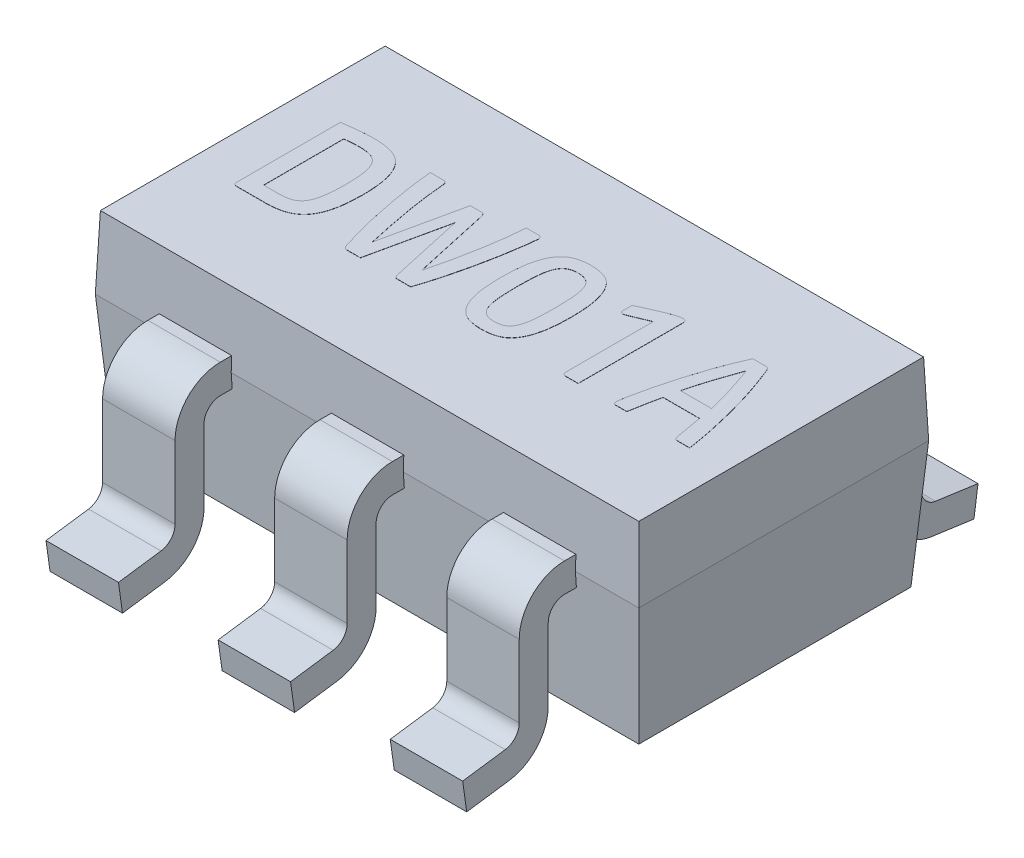
SolidWorks part; units mm, degrees
ref_plane "Front" through (0, 0, 0) normal (0, 0, 1) x (1, 0, 0)
ref_plane "Top" through (0, 0, 0) normal (0, 1, 0) x (1, 0, 0)
ref_plane "Right" through (0, 0, 0) normal (1, 0, 0) x (0, 0, -1)
sketch "Sketch1" plane through (0, 0, 0) normal (0, 1, 0) x (1, 0, 0)
  line L1 (-1.5, -0.8) -> (1.5, -0.8)
  line L2 (-1.5, -0.8) -> (-1.5, 0.8)
  line L3 (-1.5, 0.8) -> (1.5, 0.8)
  line L4 (1.5, -0.8) -> (1.5, 0.8)
  line L5 (-1.5, -0.8) -> (1.5, 0.8) construction
  line L6 (-1.5, 0.8) -> (1.5, -0.8) construction
  point P0 (0, 0)
  dimension "D1" = 3
  dimension "D2" = 1.6
extrude "Extrude1" add sketch "Sketch1" along normal blind 0.4 draft 2 and the other way blind 0.7 draft 4
ref_plane "Plane1" through (0.95, 0, 0) normal (1, 0, 0) x (0, 0, -1)
sketch "Sketch5" plane through (0.95, 0, 0) normal (1, 0, 0) x (0, 0, -1)
  line L0 (0, 0.08) -> (-0.86, 0.08)
  line L1 (-1.11, -0.17) -> (-1.11, -0.5694)
  line L2 (-1.1875, -0.6586) -> (-1.4223, -0.6916)
  line L3 (0, -0.08) -> (-0.86, -0.08)
  line L4 (0, 0.08) -> (0, -0.08) construction
  line L5 (-1.4223, -0.6916) -> (-1.4, -0.85)
  line L6 (-0.95, -0.17) -> (-0.95, -0.5694)
  line L7 (-1.1652, -0.817) -> (-1.4, -0.85)
  line L9 (10.6727, 0) -> (-10.6727, 0) construction
  line L10 (-0.7511, -0.7) -> (0.7511, -0.7) construction
  line L12 (0, 3.8593) -> (0, -3.8593) construction
  line L13 (1.1652, -0.817) -> (1.4, -0.85)
  line L14 (0.95, -0.17) -> (0.95, -0.5694)
  line L15 (1.4223, -0.6916) -> (1.4, -0.85)
  line L16 (0, -0.08) -> (0.86, -0.08)
  line L17 (1.1875, -0.6586) -> (1.4223, -0.6916)
  line L18 (1.11, -0.17) -> (1.11, -0.5694)
  line L19 (0, 0.08) -> (0.86, 0.08)
  arc A0 (-1.11, -0.5694) -> (-1.1875, -0.6586) centre (-1.2, -0.5694) cw
  arc A1 (-0.86, 0.08) -> (-1.11, -0.17) centre (-0.86, -0.17) ccw
  arc A2 (-0.86, -0.08) -> (-0.95, -0.17) centre (-0.86, -0.17) ccw
  arc A3 (-0.95, -0.5694) -> (-1.1652, -0.817) centre (-1.2, -0.5694) cw
  arc A4 (0.95, -0.5694) -> (1.1652, -0.817) centre (1.2, -0.5694) ccw
  arc A5 (0.86, -0.08) -> (0.95, -0.17) centre (0.86, -0.17) cw
  arc A6 (0.86, 0.08) -> (1.11, -0.17) centre (0.86, -0.17) cw
  arc A7 (1.11, -0.5694) -> (1.1875, -0.6586) centre (1.2, -0.5694) ccw
  arc A8 (-0.86, 0.08) -> (-1.11, -0.17) centre (-0.86, -0.17) ccw construction
  arc A9 (-1.11, -0.5694) -> (-1.1875, -0.6586) centre (-1.2, -0.5694) cw construction
  point P13 (-1.11, -0.6477)
  dimension "D6" = 0.15
  dimension "D7" = 0.45
  dimension "D5" = 0.25
  dimension "D1" = 0.16
  dimension "D2" = 0.08
  dimension "D3" = 8
  dimension "D4" = 1.4
extrude "Extrude3" add sketch "Sketch5" along normal mid plane 0.4
pattern_linear "LPattern3" count 3 spacing 0.95 along (-1, 0, 0) of "Extrude3"
sketch "Sketch6" plane through (0, 0.4, 0) normal (0, 1, 0) x (1, 0, 0)
  line L0 (-1.486, -0.295) -> (1.486, -0.295) construction
  line L1 (-1.486, 0.786) -> (-1.486, -0.786) construction
  line L2 (1.486, -0.786) -> (1.486, 0.786) construction
  text T0 "DW01A" font "@Adobe Fan Heiti Std B" height 0.6
extrude "Boss-Extrude1" add sketch "Sketch6" along normal blind 0.001
